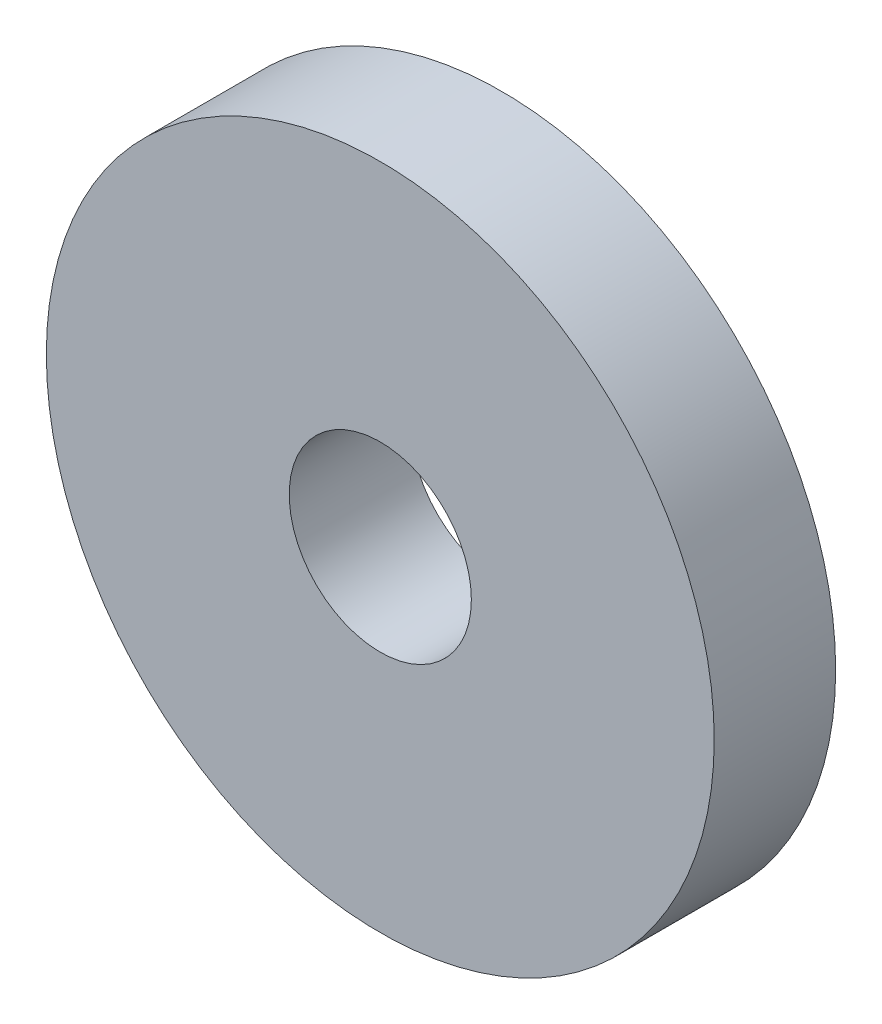
SolidWorks part; units mm, degrees
ref_plane "Front" through (0, 0, 0) normal (0, 0, 1) x (1, 0, 0)
ref_plane "Top" through (0, 0, 0) normal (0, 1, 0) x (1, 0, 0)
ref_plane "Right" through (0, 0, 0) normal (1, 0, 0) x (0, 0, -1)
sketch "Sketch1" plane through (0, 0, 0) normal (0, 0, 1) x (1, 0, 0)
  circle A0 centre (0, 0) radius 5.5
extrude "Extrude1" add sketch "Sketch1" along normal blind 2
sketch "Sketch2" plane through (0, 0, 2) normal (0, 0, 1) x (1, 0, 0)
  circle A0 centre (0, 0) radius 1.5
extrude "Cut-Extrude1" cut sketch "Sketch2" against normal through all
